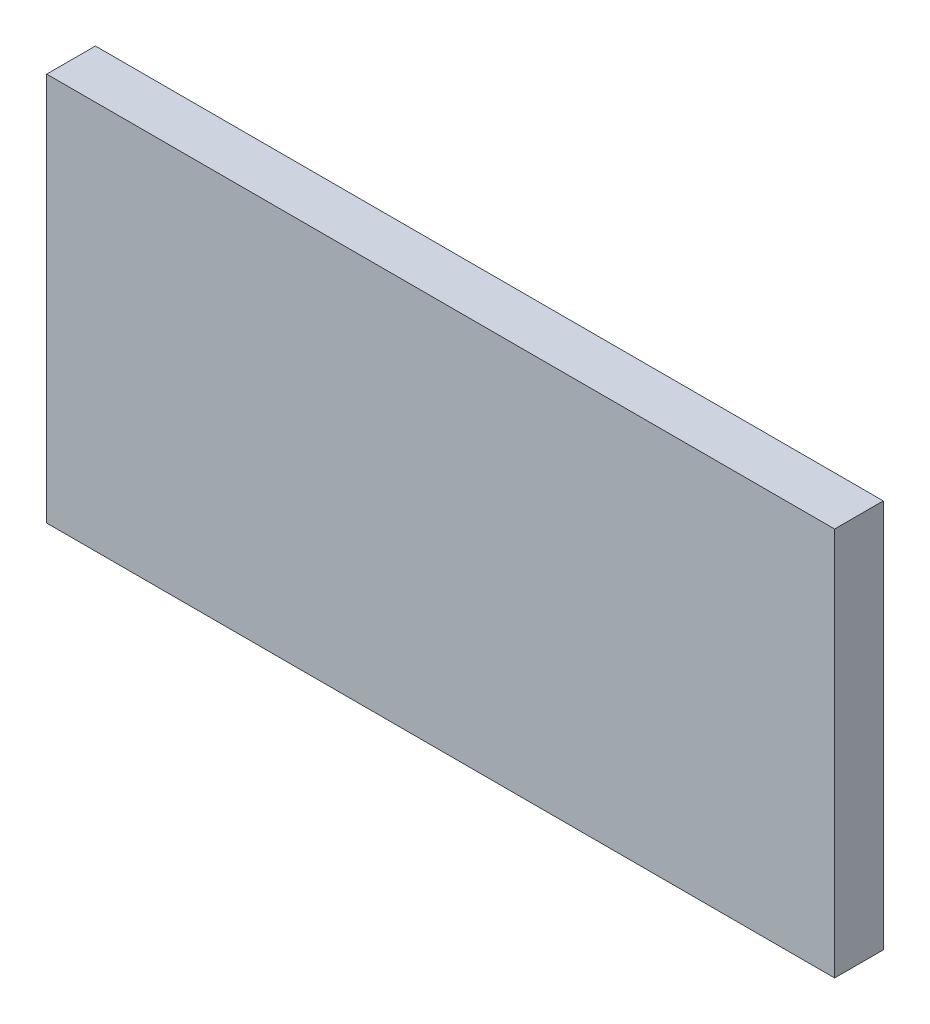
SolidWorks part; units mm, degrees
ref_plane "Front Plane" through (0, 0, 0) normal (0, 0, 1) x (1, 0, 0)
ref_plane "Top Plane" through (0, 0, 0) normal (0, 1, 0) x (1, 0, 0)
ref_plane "Right Plane" through (0, 0, 0) normal (1, 0, 0) x (0, 0, -1)
sketch "Sketch1" plane through (0, 0, -312.2833) normal (0, 0, 1) x (1, 0, 0)
  line L3 (415.0334, 113.8543) -> (415.0334, -38.3527)
  line L4 (106.6276, 113.8543) -> (415.0334, -38.3527) construction
  line L5 (120.1999, 178.3814) -> (35475.539, -35176.9577) construction
  line L6 (112.6632, -110.4166) -> (35468.0022, 35244.9225) construction
  line L7 (106.6276, -38.3527) -> (415.0334, -38.3527)
  line L11 (106.6276, 113.8543) -> (106.6276, -38.3527)
  line L12 (106.6276, 113.8543) -> (415.0334, 113.8543)
  point P0 (260.8305, 37.7508)
  dimension "D1" = 152.2071
  dimension "D3" = 308.4058
extrude "Boss-Extrude2" add sketch "Sketch1" along normal blind 19.05
